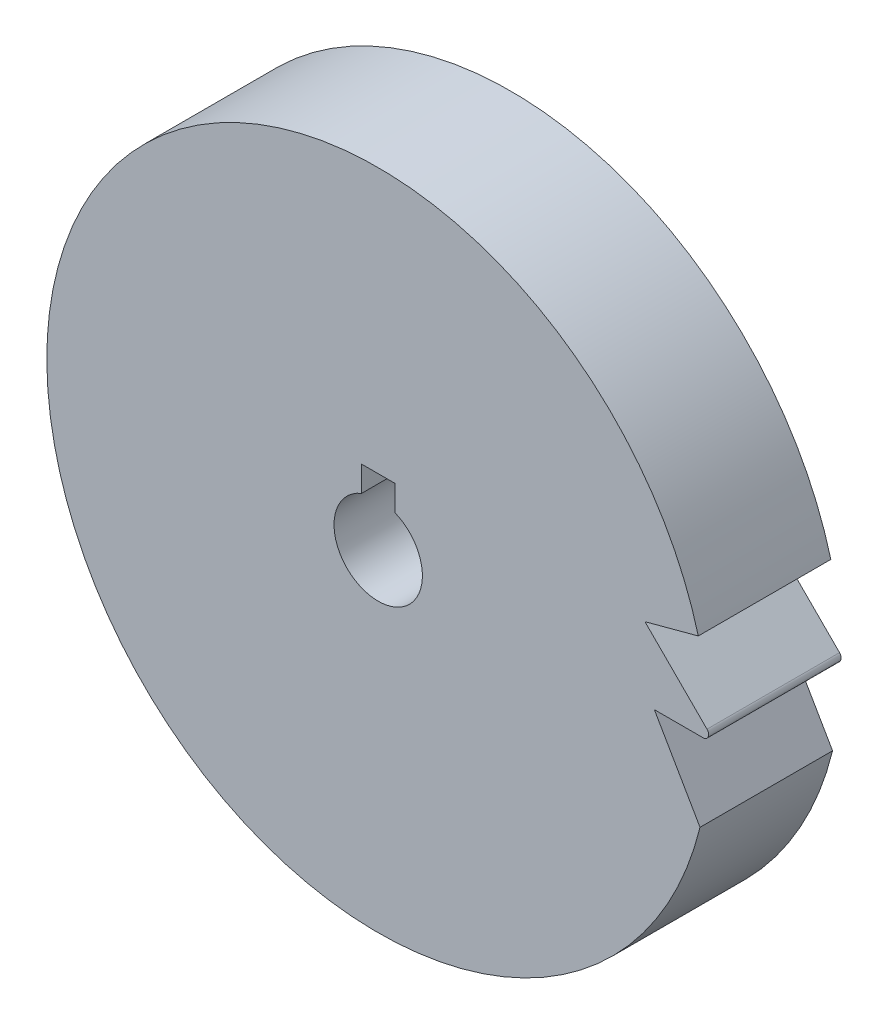
SolidWorks part; units mm, degrees
ref_plane "Front Plane" through (0, 0, 0) normal (0, 0, 1) x (1, 0, 0)
ref_plane "Top Plane" through (0, 0, 0) normal (0, 1, 0) x (1, 0, 0)
ref_plane "Right Plane" through (0, 0, 0) normal (1, 0, 0) x (0, 0, -1)
sketch "Sketch1" plane through (0, 0, 0) normal (0, 0, 1) x (1, 0, 0)
  line L0 (0, 30) -> (0, -30) construction
  line L1 (-30, 0) -> (30, 0) construction
  line L4 (0, 0) -> (33.7174, 9.0345) construction
  line L11 (-1.5, 6) -> (1.5, 6)
  line L12 (-1.5, 6) -> (-1.5, 3.7081)
  line L13 (1.5, 6) -> (1.5, 3.7081)
  circle A0 centre (0, 0) radius 30
  arc A2 (-1.5, 3.7081) -> (1.5, 3.7081) centre (0, 0) ccw
  dimension "D2" = 15
extrude "Extrude1" add sketch "Sketch1" along normal blind 12
sketch "Sketch2" plane through (0, 0, 12) normal (0, 0, 1) x (1, 0, 0)
  line L0 (25, 0) -> (29.4115, 0)
  line L1 (24.1481, 6.4705) -> (34.5917, 9.2688)
  line L3 (24.1481, 6.4705) -> (29.7651, 0.8536)
  line L8 (25, 0) -> (29.5753, -7.9247)
  line L10 (34.5917, 9.2688) -> (29.5753, -7.9247)
  arc A3 (29.4115, 0) -> (29.7651, 0.8536) centre (29.4115, 0.5) ccw
  dimension "D5" = 0.5
  dimension "D1" = 15
  dimension "D2" = 60
extrude "Cut-Extrude1" cut sketch "Sketch2" against normal blind 12
